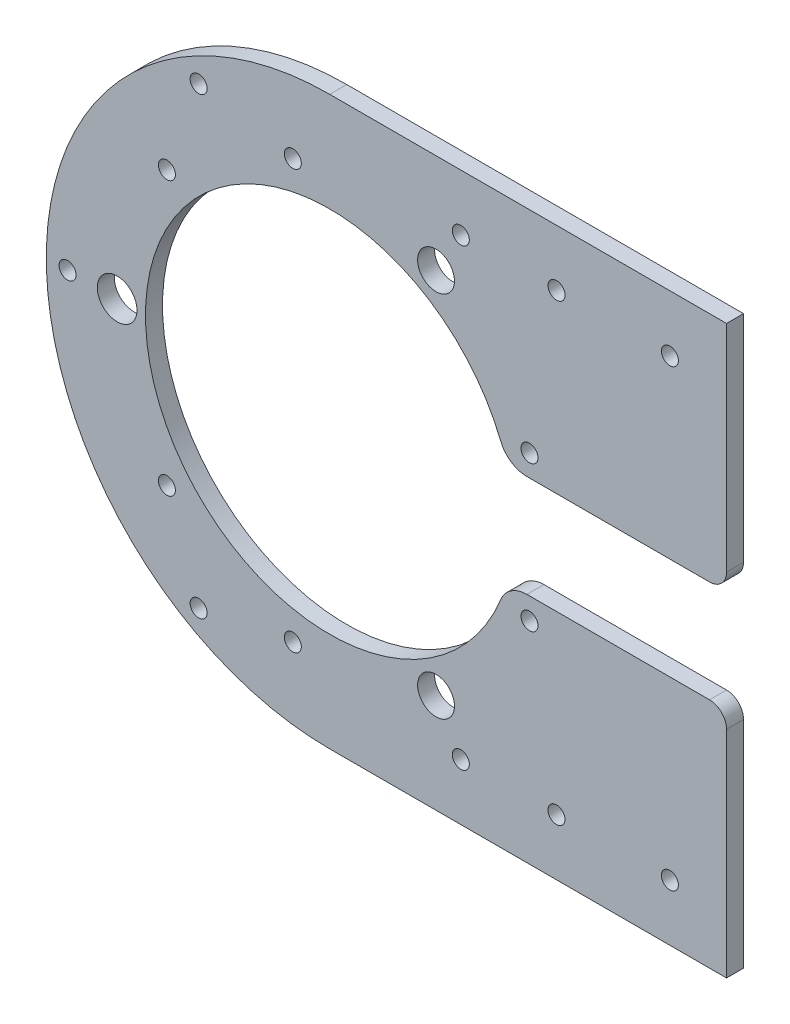
SolidWorks part; units mm, degrees
ref_plane "Front Plane" through (0, 0, 0) normal (0, 0, 1) x (1, 0, 0)
ref_plane "Top Plane" through (0, 0, 0) normal (0, 1, 0) x (1, 0, 0)
ref_plane "Right Plane" through (0, 0, 0) normal (1, 0, 0) x (0, 0, -1)
sketch "草图1" plane through (0, 0, 0) normal (0, 0, 1) x (1, 0, 0)
  line L1 (-400, 0) -> (-312.5, 0) construction
  line L3 (-10, 50) -> (-350, 50)
  line L5 (-10, -50) -> (-350, -50)
  arc A1 (-350, 50) -> (-350, -50) centre (-350, 0) ccw
  circle A2 centre (-350, 0) radius 37.5 construction
  circle A3 centre (-387.5, 0) radius 1.5
  circle A4 centre (-378.7267, 24.1045) radius 1.5
  circle A5 centre (-356.5118, 36.9303) radius 1.5
  circle A6 centre (-331.25, 32.476) radius 1.5
  circle A7 centre (-314.7615, 12.8258) radius 1.5
  circle A8 centre (-314.7615, -12.8258) radius 1.5
  circle A9 centre (-331.25, -32.476) radius 1.5
  circle A10 centre (-356.5118, -36.9303) radius 1.5
  circle A11 centre (-378.7267, -24.1045) radius 1.5
  circle A12 centre (-350, 0) radius 32.5
  circle A13 centre (-10, 0) radius 37.5 construction
  circle A14 centre (-10, 0) radius 32.5
  circle A15 centre (18.7267, -24.1045) radius 1.5
  circle A16 centre (-3.4882, -36.9303) radius 1.5
  circle A17 centre (-28.75, -32.476) radius 1.5
  circle A18 centre (-45.2385, -12.8258) radius 1.5
  circle A19 centre (-45.2385, 12.8258) radius 1.5
  circle A20 centre (-28.75, 32.476) radius 1.5
  circle A21 centre (-3.4882, 36.9303) radius 1.5
  circle A22 centre (18.7267, 24.1045) radius 1.5
  circle A23 centre (27.5, 0) radius 1.5
  arc A24 (-10, 50) -> (-10, -50) centre (-10, 0) cw
  point P5 (0, 0)
  point P30 (-350, 0)
  point P54 (-10, 0)
  dimension "D1" = 75
  dimension "D2" = 3
  dimension "D4" = 32.5
  dimension "D5" = 65
  dimension "D3" = 9
extrude "凸台-拉伸1" add sketch "草图1" along normal blind 3
sketch "草图2" plane through (0, 0, 3) normal (0, 0, 1) x (1, 0, 0)
  line L1 (-325.5, -9) -> (-309.5, -9)
  line L2 (-325.5, -9) -> (-325.5, 9)
  line L3 (-325.5, 9) -> (-309.5, 9)
  line L4 (-309.5, -9) -> (-309.5, 9)
  line L5 (-325.5, -9) -> (-309.5, 9) construction
  line L6 (-325.5, 9) -> (-309.5, -9) construction
  circle A1 centre (-331.2509, 32.4764) radius 3.25
  circle A2 centre (-387.5, -0.001) radius 3.5
  circle A3 centre (-331.2491, -32.4755) radius 3.25
  circle A4 centre (-350, 0) radius 32.5 construction
  point P9 (-317.5, 0)
  dimension "D1" = 6.5
  dimension "D2" = 7
  dimension "D3" = 6.5
  dimension "D4" = 18
  dimension "D5" = 16
extrude "切除-拉伸2" cut sketch "草图2" against normal blind 10
fillet "圆角2" radius 5 2 edges at (-318.771, -9, 1.5) (-318.771, 9, 1.5)
fillet "圆角3" radius 2 2 edges at (-309.5, 9, 1.5) (-309.5, -9, 1.5)
sketch "草图3" plane through (0, 0, 3) normal (0, 0, 1) x (1, 0, 0)
  line L0 (-180, -50) -> (-280, -50)
  line L1 (-10, -50) -> (-350, -50) construction
  line L3 (-280, -50) -> (74.6969, -50)
  line L4 (-280, -50) -> (-280, 85.6947)
  line L5 (-280, 85.6947) -> (74.6969, 85.6947)
  line L6 (74.6969, -50) -> (74.6969, 85.6947)
  arc M12 (-10, -50) -> (-10, 50) centre (-10, 0) ccw
  line M13 (-10, 50) -> (-350, 50)
  line M15 (-350, -50) -> (-10, -50)
  circle M16 centre (18.7267, 24.1045) radius 1.5
  circle M17 centre (-28.75, 32.476) radius 1.5
  circle M18 centre (-45.2385, -12.8258) radius 1.5
  circle M19 centre (-3.4882, -36.9303) radius 1.5
  circle M20 centre (-10, 0) radius 32.5
  circle M27 centre (18.7267, -24.1045) radius 1.5
  circle M28 centre (-28.75, -32.476) radius 1.5
  circle M29 centre (-45.2385, 12.8258) radius 1.5
  circle M30 centre (-3.4882, 36.9303) radius 1.5
  circle M31 centre (27.5, 0) radius 1.5
  dimension "D1" = 100
extrude "切除-拉伸3" cut sketch "草图3" against normal blind 10 contours L4 M15 M12 M13 M17 M19 M27 M29 M31 M30 M28 M20 M18 M16
sketch "草图5" plane through (0, 0, 3) normal (0, 0, 1) x (1, 0, 0)
  circle A0 centre (-350, 0) radius 46.25 construction
  circle A1 centre (-396.25, 0) radius 1.5
  dimension "D1" = 92.5
  dimension "D2" = 3
extrude "切除-拉伸4" cut sketch "草图5" against normal blind 10
sketch "草图6" plane through (0, 0, 3) normal (0, 0, 1) x (1, 0, 0)
  circle A0 centre (-396.25, 0) radius 1.5
  circle A1 centre (-373.125, 40.0537) radius 1.5
  circle A2 centre (-326.875, 40.0537) radius 1.5
  circle A3 centre (-303.75, 0) radius 1.5
  circle A4 centre (-326.875, -40.0537) radius 1.5
  circle A5 centre (-373.125, -40.0537) radius 1.5
  point P15 (-350, 0)
  dimension "D1" = 6
extrude "切除-拉伸5" cut sketch "草图6" against normal through all
sketch "草图7" plane through (0, 0, 3) normal (0, 0, 1) x (1, 0, 0)
  circle A0 centre (-309.9871, 40.0569) radius 1.5
  circle A1 centre (-289.9871, 40.0504) radius 1.5
  circle A2 centre (-309.999, -40.0509) radius 1.5
  circle A3 centre (-289.999, -40.0504) radius 1.5
extrude "切除-拉伸6" cut sketch "草图7" against normal through all
sketch "草图8" plane through (0, 0, 3) normal (0, 0, 1) x (1, 0, 0)
  line L0 (-311.5, 9) -> (-315.2114, 9) construction
  line L1 (-313.3557, 9) -> (-268.3439, 9)
  line L2 (-313.3557, 9) -> (-313.3557, -9)
  line L3 (-313.3557, -9) -> (-268.3439, -9)
  line L4 (-268.3439, 9) -> (-268.3439, -9)
  dimension "D1" = 18
extrude "切除-拉伸7" cut sketch "草图8" against normal blind 10
fillet "圆角4" radius 3 2 edges at (-280, -9, 1.5) (-280, 9, 1.5)
